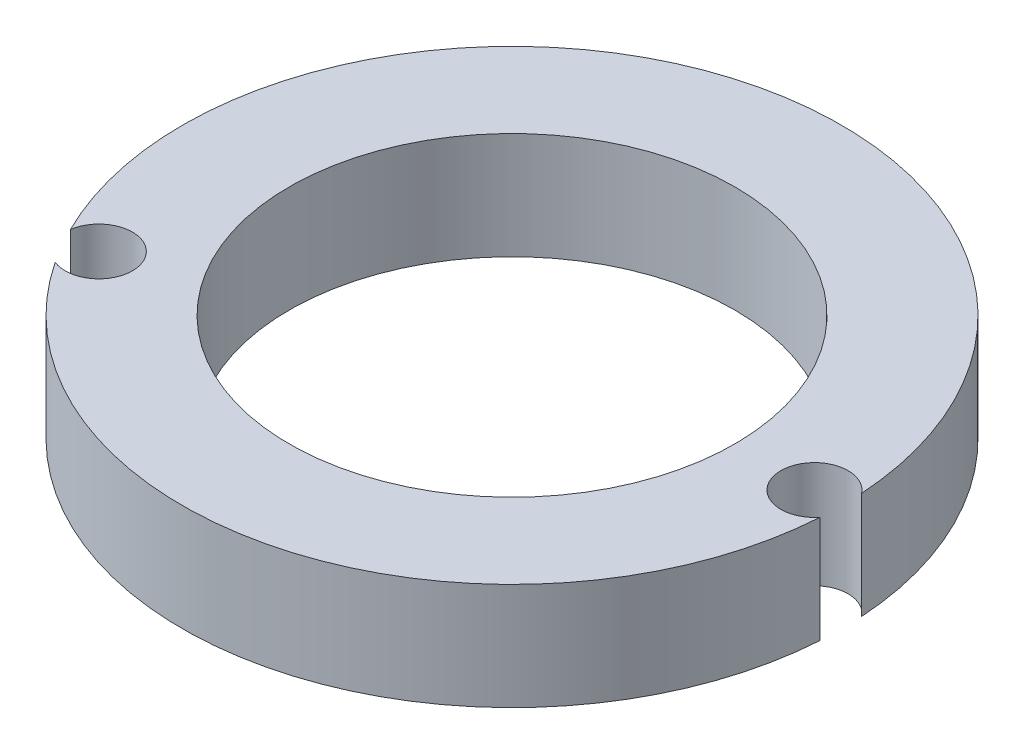
SolidWorks part; units mm, degrees
ref_plane "Front" through (0, 0, 0) normal (0, 0, 1) x (1, 0, 0)
ref_plane "Top" through (0, 0, 0) normal (0, 1, 0) x (1, 0, 0)
ref_plane "Right" through (0, 0, 0) normal (1, 0, 0) x (0, 0, -1)
sketch "Sketch1" plane through (0, 0, 0) normal (0, 0, 1) x (1, 0, 0)
  line L0 (26.51, 281.6466) -> (26.51, 268.9466)
  line L1 (0, 0) -> (26.51, 0) construction
  line L2 (0, 0) -> (0, 322.5334) construction
  line L3 (0, 322.5334) -> (26.51, 322.5334) construction
  line L4 (26.51, 0) -> (26.51, 322.5334) construction
  line L5 (0, 0) -> (39.22, 0) construction
  line L6 (0, 0) -> (0, 322.5334) construction
  line L7 (0, 322.5334) -> (39.22, 322.5334) construction
  line L8 (39.22, 0) -> (39.22, 322.5334) construction
  line L9 (39.22, 281.6466) -> (39.22, 268.9466)
  line L10 (39.22, 281.6466) -> (26.51, 281.6466)
  line L11 (39.22, 268.9466) -> (26.51, 268.9466)
  dimension "D1" = 12.7
  dimension "D3" = 26.51
  dimension "D4" = 39.22
revolve "Revolve1" add sketch "Sketch1" angle 360 about L2
sketch "Sketch2" plane through (0, 0, 0) normal (0, 1, 0) x (1, 0, 0)
  line L0 (0, 0) -> (36, 0) construction
  line L1 (0, 0) -> (-31.1769, -18) construction
  circle A0 centre (0, 0) radius 36 construction
  circle A1 centre (-31.1769, -18) radius 4
  circle A2 centre (36, 0) radius 4
  dimension "D2" = 8
  dimension "D3" = 8
  dimension "D4" = 72
  dimension "D1" = 150
extrude "Cut-Extrude3" cut sketch "Sketch2" along normal through all
